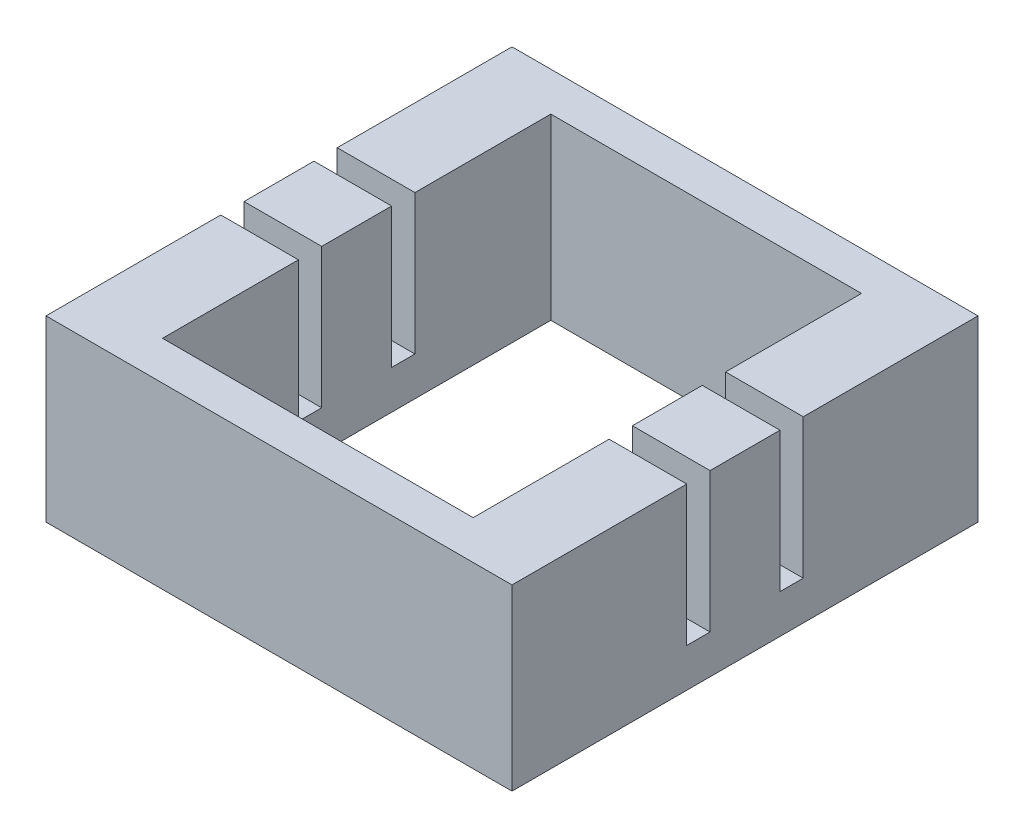
SolidWorks part; units mm, degrees
ref_plane "Front Plane" through (0, 0, 0) normal (0, 0, 1) x (1, 0, 0)
ref_plane "Top Plane" through (0, 0, 0) normal (0, 1, 0) x (1, 0, 0)
ref_plane "Right Plane" through (0, 0, 0) normal (1, 0, 0) x (0, 0, -1)
sketch "Sketch2" plane through (0, 0, 0) normal (0, 1, 0) x (1, 0, 0)
  line L9 (0, 0) -> (60, 0)
  line L10 (0, 0) -> (0, 60)
  line L11 (0, 60) -> (60, 60)
  line L12 (60, 0) -> (60, 60)
  line L13 (10, 5) -> (50, 5)
  line L14 (10, 5) -> (10, 55)
  line L15 (10, 55) -> (50, 55)
  line L16 (50, 5) -> (50, 55)
  point P9 (60, 40.0025)
  dimension "D1" = 60
  dimension "D2" = 5
  dimension "D3" = 10
  dimension "D4" = 10
  dimension "D5" = 5
  dimension "D6" = 60
extrude "Boss-Extrude2" add sketch "Sketch2" along normal blind 23
sketch "Sketch3" plane through (0, 0, 0) normal (-1, 0, 0) x (0, 0, 1)
  line L1 (-37.5, 23) -> (-34.5, 23)
  line L2 (-37.5, 23) -> (-37.5, 5)
  line L3 (-37.5, 5) -> (-34.5, 5)
  line L4 (-34.5, 23) -> (-34.5, 5)
  line L5 (-37.5, 5) -> (-60, 5) construction
  line L6 (-22.5, 23) -> (-25.5, 23)
  line L7 (-22.5, 23) -> (-22.5, 5)
  line L8 (-22.5, 5) -> (-25.5, 5)
  line L9 (-25.5, 23) -> (-25.5, 5)
  line L11 (-22.5, 5) -> (0, 5) construction
  line L13 (-34.5, 5) -> (-25.5, 5) construction
  line L15 (-60, 23) -> (-60, 0) construction
  line L16 (0, 23) -> (0, 0) construction
  line L17 (-60, 0) -> (0, 0) construction
  line L18 (-60, 23) -> (0, 23) construction
  point P4 (0, 0)
  point P5 (0, 0)
  point P12 (0, 0)
  point P14 (0, 0)
  dimension "D1" = 9
  dimension "D2" = 3
  dimension "D3" = 5
extrude "Cut-Extrude1" cut sketch "Sketch3" against normal through all
